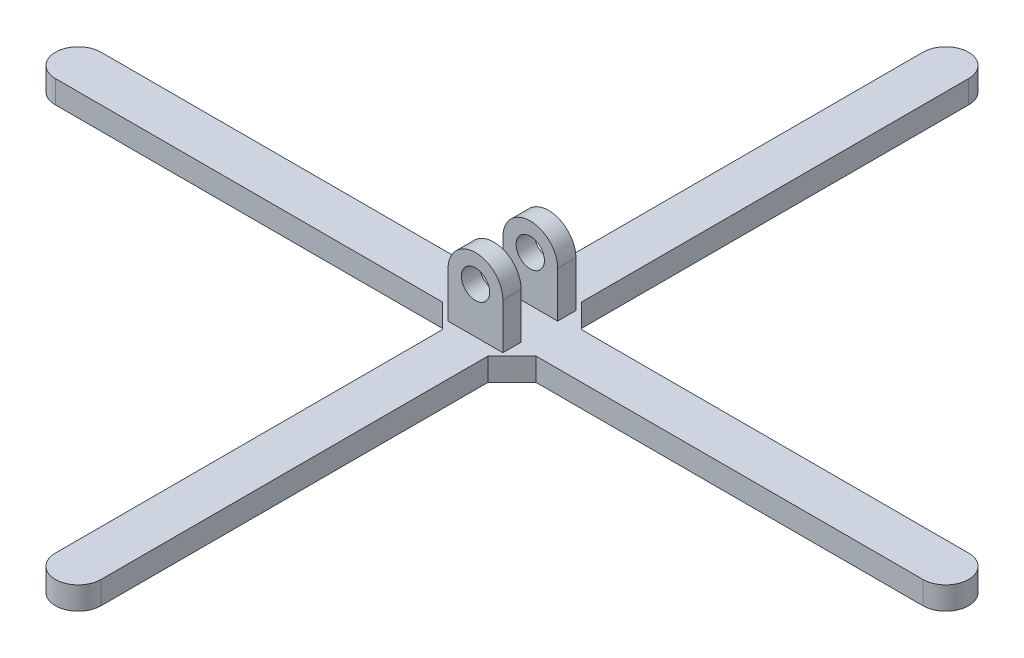
SolidWorks part; units mm, degrees
ref_plane "Front Plane" through (0, 0, 0) normal (0, 0, 1) x (1, 0, 0)
ref_plane "Top Plane" through (0, 0, 0) normal (0, 1, 0) x (1, 0, 0)
ref_plane "Right Plane" through (0, 0, 0) normal (1, 0, 0) x (0, 0, -1)
sketch "Sketch1" plane through (0, 0, 0) normal (0, 1, 0) x (1, 0, 0)
  line L0 (0, 47.5) -> (0, -47.5) construction
  line L1 (2.5, 47.5) -> (2.5, 5.1263)
  line L2 (-2.5, 47.5) -> (-2.5, 5.1263)
  line L3 (47.5, 0) -> (-47.5, 0) construction
  line L4 (47.5, -2.5) -> (5.1263, -2.5)
  line L5 (47.5, 2.5) -> (5.1263, 2.5)
  line L15 (2.5, 5.1263) -> (5.1263, 2.5)
  line L17 (5.1263, -2.5) -> (2.5, -5.1263)
  line L19 (-2.5, -5.1263) -> (-5.1263, -2.5)
  line L21 (-5.1263, 2.5) -> (-2.5, 5.1263)
  line L22 (-2.5, -5.1263) -> (-2.5, -47.5)
  line L23 (-5.1263, 2.5) -> (-47.5, 2.5)
  line L24 (2.5, -5.1263) -> (2.5, -47.5)
  line L25 (-5.1263, -2.5) -> (-47.5, -2.5)
  arc A0 (2.5, 47.5) -> (-2.5, 47.5) centre (0, 47.5) ccw
  arc A1 (-2.5, -47.5) -> (2.5, -47.5) centre (0, -47.5) ccw
  arc A2 (47.5, -2.5) -> (47.5, 2.5) centre (47.5, 0) ccw
  arc A3 (-47.5, 2.5) -> (-47.5, -2.5) centre (-47.5, 0) ccw
  point P3 (0, 0)
  point P8 (0, 50)
  point P9 (0, -50)
  point P12 (0, 0)
  point P17 (-50, 0)
  point P18 (50, 0)
  dimension "D1" = 100
  dimension "D2" = 5
  dimension "D3" = 100
  dimension "D4" = 5
extrude "Boss-Extrude1" add sketch "Sketch1" along normal blind 2.5
ref_plane "Plane1" through (0, 0, 3) normal (0, 0, 1) x (1, 0, 0)
sketch "Sketch2" plane through (0, 0, 3) normal (0, 0, 1) x (1, 0, 0)
  line L0 (2.5, 2.5) -> (-2.5, 2.5) construction
  line L1 (-3, 2.5) -> (3, 2.5)
  line L2 (-3, 2.5) -> (-3, 7.5)
  line L4 (3, 2.5) -> (3, 7.5)
  arc A0 (3, 7.5) -> (-3, 7.5) centre (0, 7.5) ccw
  circle A1 centre (0, 7.5) radius 1.55
  dimension "D1" = 3.1
  dimension "D3" = 5
  dimension "D2" = 6
extrude "Boss-Extrude2" add sketch "Sketch2" along normal mid plane 2
mirror "Mirror2" about plane through (0, 0, 0) normal (0, 0, 1) of "Boss-Extrude2"
equation "\"ScrewSize\"= 3.1mm"
